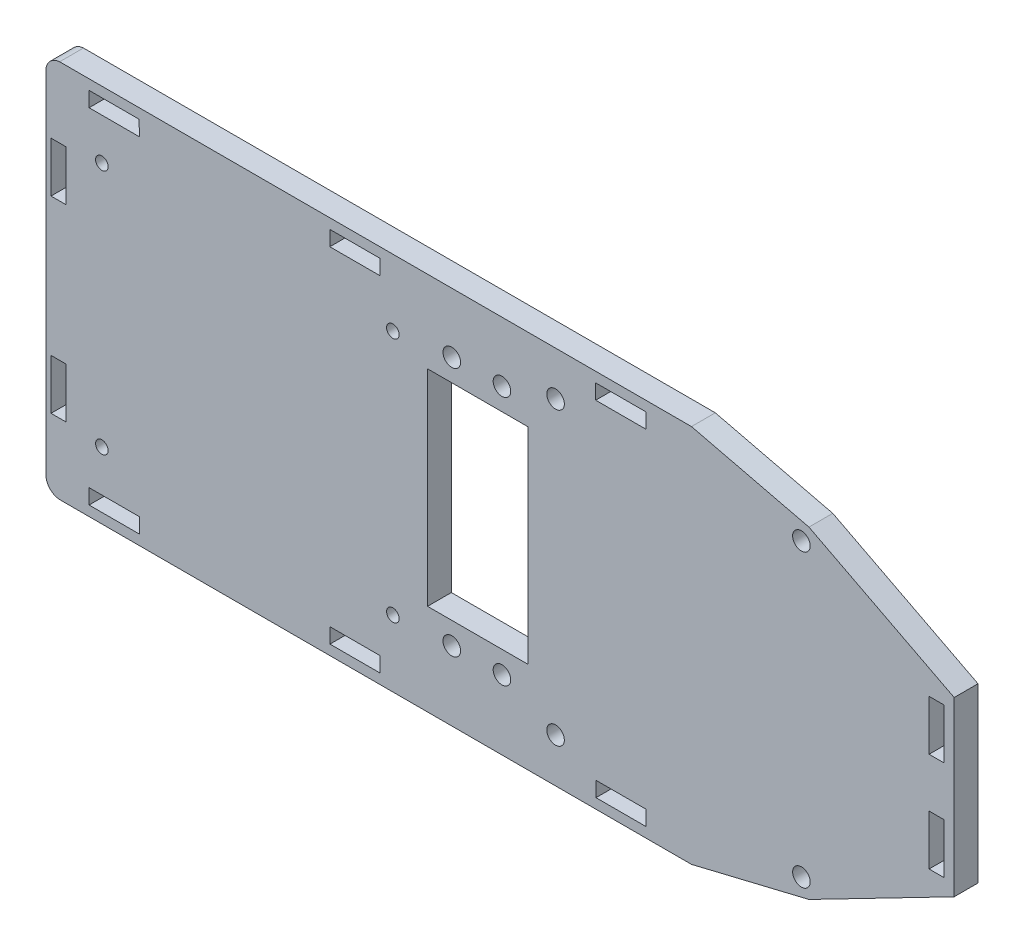
SolidWorks part; units mm, degrees
ref_plane "Front Plane" through (0, 0, 0) normal (0, 0, 1) x (1, 0, 0)
ref_plane "Top Plane" through (0, 0, 0) normal (0, 1, 0) x (1, 0, 0)
ref_plane "Right Plane" through (0, 0, 0) normal (1, 0, 0) x (0, 0, -1)
sketch "Sketch1" plane through (0, 0, 0) normal (0, 0, 1) x (1, 0, 0)
  line L1 (-90.5, -37.785) -> (90.5, -37.785)
  line L2 (-90.5, -37.785) -> (-90.5, 37.785)
  line L3 (-90.5, 37.785) -> (90.5, 37.785)
  line L4 (90.5, -37.785) -> (90.5, 37.785)
  line L5 (-90.5, -37.785) -> (90.5, 37.785) construction
  line L6 (-90.5, 37.785) -> (90.5, -37.785) construction
  point P0 (0, 0)
extrude "Boss-Extrude2" add sketch "Sketch1" along normal blind 4.75
sketch "Sketch6" plane through (0, 0, 4.75) normal (0, 0, 1) x (1, 0, 0)
  line L0 (-90.5, 0) -> (90.5, 0) construction
  line L1 (-90.5, 37.785) -> (-90.5, -37.785) construction
  line L2 (90.5, -37.785) -> (90.5, 37.785) construction
  line L3 (0, 37.785) -> (0, -37.785) construction
  line L4 (90.5, 37.785) -> (-90.5, 37.785) construction
  line L5 (-90.5, -37.785) -> (90.5, -37.785) construction
  line L6 (-90.5, 34.4318) -> (-90.5, -34.4318)
  line L7 (90.5, 17.2) -> (90.5, -17.2)
  line L10 (-21.3732, 40.787) -> (-21.3732, -34.783) construction
  line L11 (-81.9134, 32.786) -> (-71.8797, 32.7858)
  line L12 (-89.5, 23.75) -> (-86.5, 23.75)
  line L13 (-89.5, 23.75) -> (-89.5, 13.75)
  line L14 (-89.5, 13.75) -> (-86.5, 13.75)
  line L15 (-86.5, 23.75) -> (-86.5, 13.75)
  line L16 (-89.5, -13.75) -> (-86.5, -13.75)
  line L17 (-89.5, -13.75) -> (-89.5, -23.75)
  line L18 (-89.5, -23.75) -> (-86.5, -23.75)
  line L19 (-86.5, -13.75) -> (-86.5, -23.75)
  line L20 (-33.9297, 32.785) -> (-33.9309, 35.785)
  line L21 (-33.9297, 32.785) -> (-23.9273, 32.7887)
  line L22 (-33.9309, 35.785) -> (-23.931, 35.785)
  line L23 (-23.9273, 32.7887) -> (-23.931, 35.785)
  line L24 (-71.8797, 32.7858) -> (-71.9473, 35.785)
  line L25 (-81.9134, 32.786) -> (-81.9472, 35.785)
  line L26 (-81.9472, 35.785) -> (-71.9473, 35.785)
  line L27 (-81.9134, -32.785) -> (-71.8797, -32.7852)
  line L28 (-71.9135, -35.785) -> (-71.8797, -32.7852)
  line L29 (-81.9135, -35.785) -> (-71.9135, -35.785)
  line L30 (-81.9135, -35.785) -> (-81.9134, -32.785)
  line L31 (-33.9026, -35.7859) -> (-23.8868, -35.7861)
  line L32 (-33.9026, -35.7859) -> (-33.9037, -32.7859)
  line L33 (-23.8868, -35.7861) -> (-23.8868, -32.7861)
  line L34 (-33.9037, -32.7859) -> (-23.8868, -32.7861)
  line L35 (85.5, 14.9) -> (85.5, 4.9)
  line L36 (88.5, 14.9) -> (88.5, 4.9)
  line L37 (85.5, 4.9) -> (88.5, 4.9)
  line L38 (85.5, 14.9) -> (88.5, 14.9)
  line L40 (29.053, 32.7887) -> (29.053, 35.785)
  line L41 (19.053, 32.7887) -> (29.053, 32.7887)
  line L42 (19.053, 32.7887) -> (19.053, 35.785)
  line L43 (19.053, 35.785) -> (29.053, 35.785)
  line L44 (19.1132, -32.785) -> (29.053, -32.785)
  line L45 (19.1132, -35.785) -> (19.1132, -32.785)
  line L46 (19.1132, -35.785) -> (29.053, -35.785)
  line L47 (29.053, -35.785) -> (29.053, -32.785)
  line L50 (-87.3981, 37.785) -> (38.1419, 37.785)
  line L51 (-14.4594, 21.457) -> (5.5406, 21.457)
  line L52 (-14.4594, 21.457) -> (-14.4594, -19.543)
  line L53 (-14.4594, -19.543) -> (5.5406, -19.543)
  line L54 (5.5406, 21.457) -> (5.5406, -19.543)
  line L58 (-87.3981, -37.785) -> (38.1419, -37.785)
  line L60 (85.5, -14.9) -> (88.5, -14.9)
  line L61 (88.5, -14.9) -> (88.5, -4.9)
  line L62 (85.5, -4.9) -> (88.5, -4.9)
  line L63 (85.5, -14.9) -> (85.5, -4.9)
  line L64 (38.1419, -37.785) -> (61.5528, -32.1352)
  line L65 (61.5528, -32.1352) -> (90.5, -17.2)
  line L66 (38.1419, 37.785) -> (61.5528, 32.14)
  line L67 (61.5528, 32.14) -> (90.5, 17.2)
  arc A0 (-87.3981, 37.785) -> (-90.5, 34.4318) centre (-87.5923, 34.8533) ccw
  arc A1 (-90.5, -34.4318) -> (-87.3981, -37.785) centre (-87.5923, -34.8533) ccw
  circle A8 centre (-9.6294, 25.857) radius 1.75
  circle A9 centre (0.3706, 25.857) radius 1.75
  circle A10 centre (0.3706, -23.943) radius 1.75
  circle A11 centre (-9.6294, -23.943) radius 1.75
  circle A12 centre (11.053, -29) radius 1.75
  circle A13 centre (11.053, 29) radius 1.75
  circle A14 centre (60.053, -29) radius 1.75
  circle A15 centre (60.053, 29) radius 1.75
  circle A16 centre (-79.3732, 24.5) radius 1.25
  circle A17 centre (-79.3732, -24.5) radius 1.25
  circle A18 centre (-21.3732, -24.5) radius 1.25
  circle A19 centre (-21.3732, 24.5) radius 1.25
  point P21 (90.5, 0)
  dimension "D1" = 58
  dimension "D3" = 49
  dimension "D2" = 29
  dimension "D4" = 58
  dimension "D10" = 2
  dimension "D11" = 4.4
  dimension "D16" = 32.14
  dimension "D17" = 2
  dimension "D5" = 2
  dimension "D6" = 2
  dimension "D7" = 2
  dimension "D8" = 43
  dimension "D9" = 49.8
  dimension "D12" = 4.4
  dimension "D13" = 58
  dimension "D14" = 49
  dimension "D15" = 24.5
  dimension "D18" = 1
extrude "Cut-Extrude7" cut sketch "Sketch6" against normal blind 9
